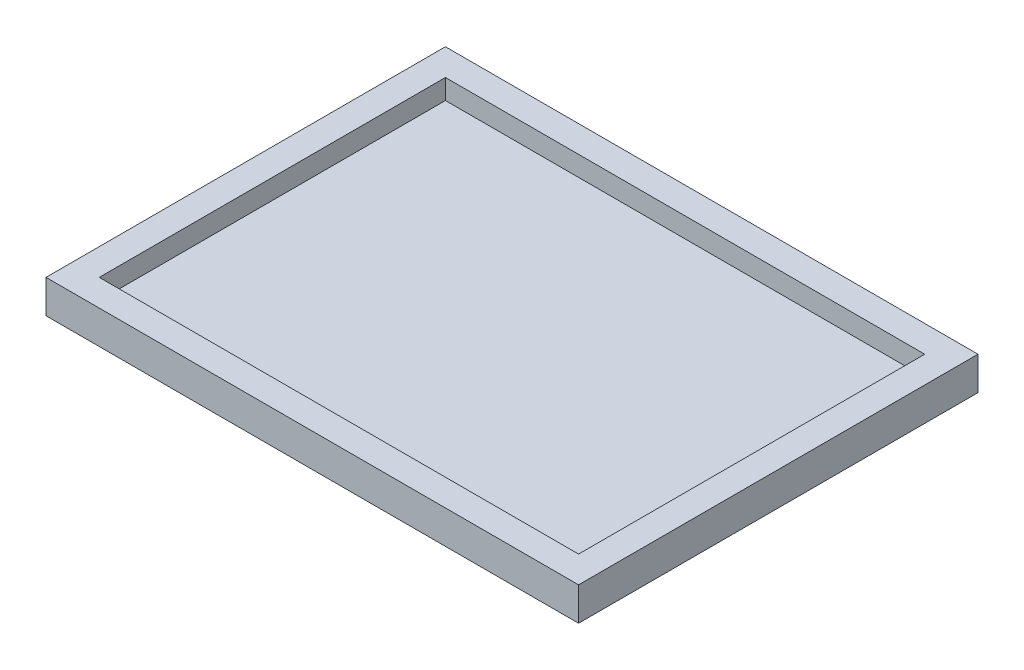
SolidWorks part; units mm, degrees
material "Maple"
ref_plane "Front Plane" through (0, 0, 0) normal (0, 0, 1) x (1, 0, 0)
ref_plane "Top Plane" through (0, 0, 0) normal (0, 1, 0) x (1, 0, 0)
ref_plane "Right Plane" through (0, 0, 0) normal (1, 0, 0) x (0, 0, -1)
sketch "Sketch1" plane through (0, 0, 0) normal (0, 1, 0) x (1, 0, 0)
  line L1 (0, 0) -> (400, 0)
  line L2 (0, 0) -> (0, 300)
  line L3 (0, 300) -> (400, 300)
  line L4 (400, 0) -> (400, 300)
  dimension "D1" = 300
  dimension "D2" = 400
extrude "Boss-Extrude1" add sketch "Sketch1" along normal blind 10
sketch "Sketch2" plane through (0, 10, 0) normal (0, 1, 0) x (1, 0, 0)
  line L1 (0, 300) -> (400, 300)
  line L2 (0, 300) -> (0, 0)
  line L3 (0, 0) -> (400, 0)
  line L4 (400, 300) -> (400, 0)
  line L5 (20, 280) -> (380, 280)
  line L6 (20, 280) -> (20, 20)
  line L7 (20, 20) -> (380, 20)
  line L8 (380, 280) -> (380, 20)
  dimension "D1" = 20
  dimension "D2" = 20
  dimension "D3" = 20
  dimension "D4" = 20
extrude "Boss-Extrude2" add sketch "Sketch2" along normal blind 15
